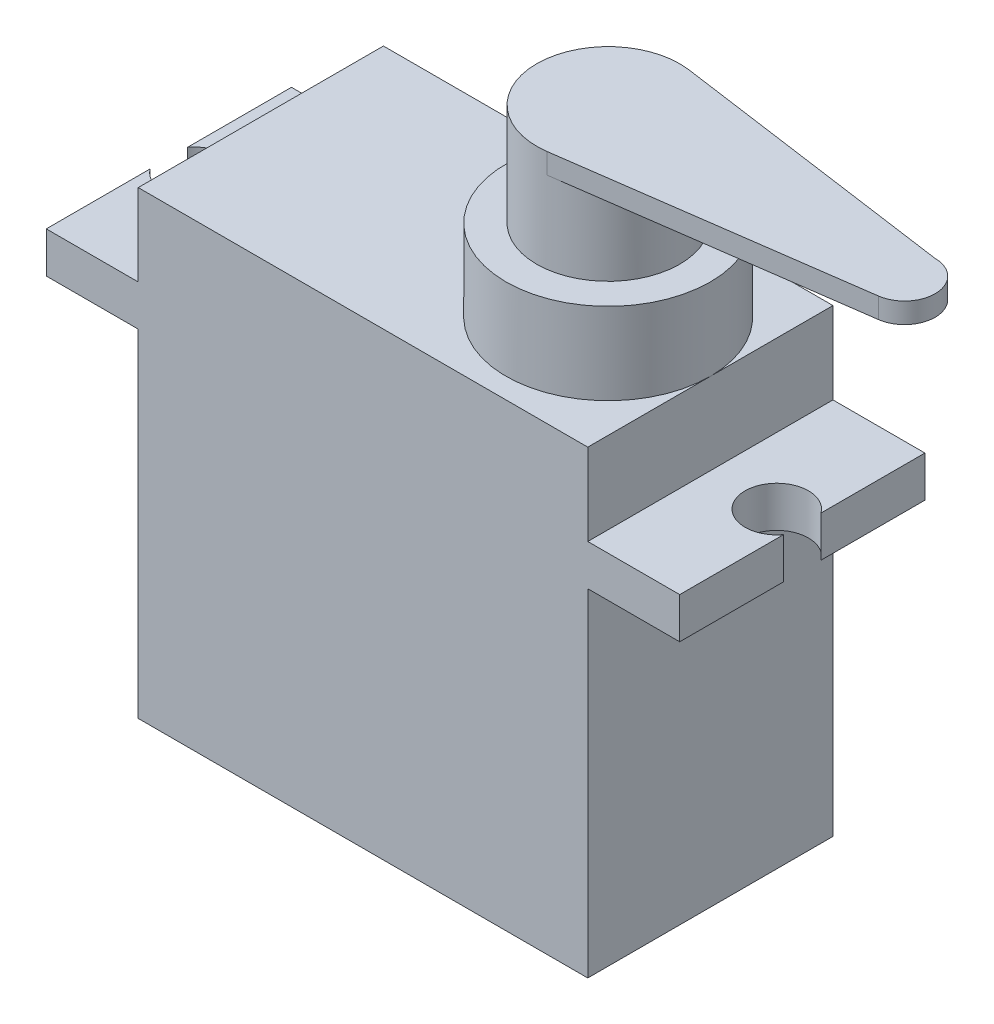
SolidWorks part; units mm, degrees
ref_plane "Front Plane" through (0, 0, 0) normal (0, 0, 1) x (1, 0, 0)
ref_plane "Top Plane" through (0, 0, 0) normal (0, 1, 0) x (1, 0, 0)
ref_plane "Right Plane" through (0, 0, 0) normal (1, 0, 0) x (0, 0, -1)
sketch "Sketch1" plane through (0, 0, 0) normal (0, 1, 0) x (1, 0, 0)
  line L0 (0, 16.773) -> (0, -16.7901) construction
  line L1 (-11, 6) -> (11, 6)
  line L2 (-11, 6) -> (-11, -6)
  line L3 (-11, -6) -> (11, -6)
  line L4 (11, 6) -> (11, -6)
  line L5 (-20.9372, 0) -> (19.3858, 0) construction
  dimension "D1" = 22
  dimension "D2" = 12
extrude "Boss-Extrude1" add sketch "Sketch1" along normal blind 16.5
sketch "Sketch2" plane through (0, 16.5, 0) normal (0, 1, 0) x (1, 0, 0)
  line L0 (0, 12.1606) -> (0, -13.204) construction
  line L1 (-15.5, 6) -> (15.5, 6)
  line L2 (-15.5, 6) -> (-15.5, 0.9165)
  line L3 (-15.5, -6) -> (15.5, -6)
  line L4 (15.5, 6) -> (15.5, 0.9165)
  line L5 (-20.5202, 0) -> (23.2529, 0) construction
  line L6 (11, 6) -> (-11, 6) construction
  line L7 (-15.5, -0.9165) -> (-15.5, -6)
  line L8 (15.5, -0.9165) -> (15.5, -6)
  arc A0 (-15.5, -0.9165) -> (-15.5, 0.9165) centre (-14.25, 0) ccw
  arc A1 (15.5, -0.9165) -> (15.5, 0.9165) centre (14.25, 0) cw
  dimension "D2" = 3.1
  dimension "D1" = 31
  dimension "D3" = 12.7
extrude "Boss-Extrude2" add sketch "Sketch2" along normal blind 2
sketch "Sketch4" plane through (0, 18.5, 0) normal (0, 1, 0) x (1, 0, 0)
  line L4 (-11, 6) -> (-11, -6)
  line L5 (11, 6) -> (-11, 6)
  line L18 (11, -6) -> (11, 6)
  line L19 (-11, -6) -> (11, -6)
  line L20 (-11, 6) -> (-11, -6)
  line L21 (11, 6) -> (-11, 6)
  line L22 (11, -6) -> (11, 6)
  line L23 (-11, -6) -> (11, -6)
  dimension "D2" = 0
extrude "Boss-Extrude3" add sketch "Sketch4" along normal blind 4
sketch "Sketch5" plane through (0, 22.5, 0) normal (0, 1, 0) x (1, 0, 0)
  line L0 (11, -6) -> (11, 6) construction
  line L1 (-15.5784, 0) -> (19.468, 0) construction
  circle A0 centre (6, 0) radius 5
  dimension "D1" = 10
extrude "Boss-Extrude4" add sketch "Sketch5" along normal blind 4
sketch "Sketch7" plane through (0, 26.5, 0) normal (0, 1, 0) x (1, 0, 0)
  circle A0 centre (6, 0) radius 3.5
  circle A1 centre (6, 0) radius 5 construction
  dimension "D1" = 7
extrude "Boss-Extrude5" add sketch "Sketch7" along normal blind 4
sketch "Sketch8" plane through (0, 30.5, 0) normal (0, 1, 0) x (1, 0, 0)
  line L0 (5.5164, -3.4664) -> (-8.7107, -1.4816)
  line L1 (-14.0793, 0) -> (19.8529, 0) construction
  line L2 (-8.504, 1.496) -> (5.5129, 3.4659)
  line L3 (6, 7.5866) -> (6, -8.2754) construction
  line L4 (6.4836, -3.4664) -> (20.7107, -1.4816)
  line L5 (20.504, 1.496) -> (6.4871, 3.4659)
  arc A0 (5.5164, -3.4664) -> (6.4836, -3.4664) centre (6, 0) ccw
  circle A1 centre (6, 0) radius 3.5 construction
  arc A2 (-8.504, 1.496) -> (-8.7107, -1.4816) centre (-8.504, 0) ccw
  arc A3 (6.4871, 3.4659) -> (5.5129, 3.4659) centre (6, 0) ccw
  arc A4 (20.504, 1.496) -> (20.7107, -1.4816) centre (20.504, 0) cw
  dimension "D1" = 16
  dimension "D2" = 82
extrude "Boss-Extrude6" add sketch "Sketch8" along normal blind 1
sketch "Sketch10" plane through (0, 31.5, 0) normal (0, 1, 0) x (1, 0, 0)
  line L0 (-8.7107, -1.4816) -> (5.5164, -3.4664) construction
  line L1 (5.5129, 3.4659) -> (-8.504, 1.496) construction
  line L2 (-8.7107, -1.4816) -> (5.5164, -3.4664)
  line L3 (5.5129, 3.4659) -> (-8.504, 1.496)
  arc A0 (-8.504, 1.496) -> (-8.7107, -1.4816) centre (-8.504, 0) ccw construction
  arc A1 (-8.504, 1.496) -> (-8.7107, -1.4816) centre (-8.504, 0) ccw
  circle A2 centre (6, 0) radius 3.5 construction
  arc A3 (5.5129, 3.4659) -> (5.5164, -3.4664) centre (6, 0) ccw
extrude "Cut-Extrude2" cut sketch "Sketch10" against normal up to next
